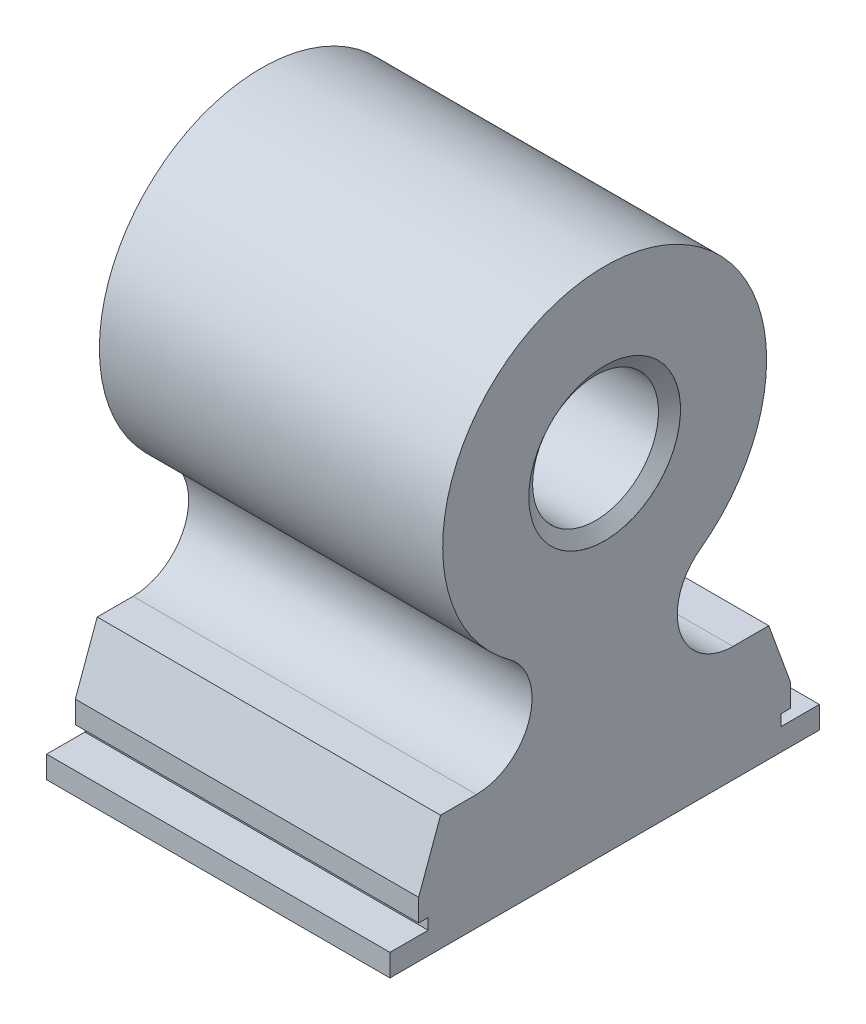
SolidWorks part; units mm, degrees
extrude "Body" add sketch "BodySke" along normal blind 9.4234
sketch "BodySke" plane through (0, 0, 0) normal (1, 0, 0) x (0, 0, -1)
  line L0 (-5.8928, -9.525) -> (5.8928, -9.525)
  line L1 (5.8928, -9.525) -> (5.8928, -8.9154)
  line L2 (5.8928, -8.9154) -> (4.8429, -8.9154)
  line L3 (-5.8928, -9.525) -> (-5.8928, -8.9154)
  line L4 (-5.8928, -8.9154) -> (-4.8429, -8.9154)
  line L5 (4.8429, -8.9154) -> (4.8429, -8.6106)
  line L6 (-4.8429, -8.9154) -> (-4.8429, -8.6106)
  line L7 (4.8429, -8.6106) -> (5.1054, -8.6106)
  line L8 (-4.8429, -8.6106) -> (-5.1054, -8.6106)
  line L9 (-3.5204, -6.35) -> (-4.5045, -6.35)
  line L10 (0, -0.7925) -> (4.5045, -0.7925) construction
  line L11 (4.5045, -6.35) -> (3.5204, -6.35)
  line L12 (0, 7.62) -> (0, -11.43) construction
  line L13 (7.62, 0) -> (-7.62, 0) construction
  line L14 (1.9939, -2.8908) -> (1.9939, -7.62) construction
  line L15 (-1.9939, -2.8908) -> (-1.9939, -7.62) construction
  line L16 (4.5045, -6.35) -> (5.1054, -8.001)
  line L17 (5.1054, -8.001) -> (5.1054, -8.6106)
  line L18 (-4.5045, -6.35) -> (-5.1054, -8.001)
  line L19 (-5.1054, -8.001) -> (-5.1054, -8.6106)
  circle A0 centre (0, 0) radius 1.7272
  arc A1 (2.6205, -3.5904) -> (-2.6205, -3.5904) centre (0, 0) ccw
  arc A2 (3.5204, -6.35) -> (2.6205, -3.5904) centre (3.5204, -4.8235) cw
  arc A3 (-2.6205, -3.5904) -> (-3.5204, -6.35) centre (-3.5204, -4.8235) cw
  dimension "Thread_min" = 3.4544
  dimension "C_dia" = 8.89
  dimension "J_dim" = 3.9878
  dimension "E_dim" = 11.7856
  dimension "D_dim" = 3.175
  dimension "Clinch_ht" = 0.6096
  dimension "Side_ht" = 0.6096
  dimension "Groove_wid" = 0.3048
  dimension "A_dim" = 10.2108
  dimension "Groove_overall" = 9.6859
  dimension "F_dim" = 9.525
  dimension "D12" = 20
  dimension "Advance" = 0.7925
cosmetic thread "ThreadCosmetic" [suppressed]
revolve "EndChamfer" cut sketch "EndChamferSke" angle 360 about L11
sketch "EndChamferSke" plane through (0, 0, 0) normal (0, 0, 1) x (1, 0, 0)
  line L0 (-0.254, 2.0828) -> (0.0025, 2.0828)
  line L2 (0.0025, 2.0828) -> (0.2514, 1.7272)
  line L3 (0.2514, 1.7272) -> (-0.254, 1.7272)
  line L4 (-0.254, 1.7272) -> (-0.254, 2.0828)
  line L5 (9.6774, 2.0828) -> (9.4209, 2.0828)
  line L6 (9.4209, 2.0828) -> (9.172, 1.7272)
  line L7 (9.172, 1.7272) -> (9.6774, 1.7272)
  line L8 (9.6774, 1.7272) -> (9.6774, 2.0828)
  line L9 (0, 4.445) -> (0, -3.5904) construction
  line L10 (9.4234, -3.5904) -> (9.4234, 4.445) construction
  line L11 (-5.1059, 0) -> (14.0173, 0) construction
  line L12 (9.4234, 0) -> (0, 0) construction
  dimension "Thread_min" = 3.4544
  dimension "D3" = 0.254
  dimension "D4" = 0.254
  dimension "Thread_nominal" = 4.1656
  dimension "D2" = 34.99
ref_plane "Plane1" through (0, 0, 0) normal (0, 0, 1) x (1, 0, 0)
ref_plane "Plane2" through (0, 0, 0) normal (0, 1, 0) x (1, 0, 0)
ref_plane "Plane3" through (0, 0, 0) normal (1, 0, 0) x (0, 0, -1)
sketch "ThdSchSke" [suppressed] plane through (0, 0, 0) normal (0, 0, 1) x (1, 0, 0)
  line L0 (-1.2331, 0) -> (11.43, 0) construction
  line L1 (6.0414, 0) -> (0.207, 0) construction
  line L2 (0.0025, 1.7272) -> (0.0025, -1.4224) construction
  line L3 (0.0025, -1.4224) -> (0.2071, -1.1303)
  line L4 (0.207, -1.1303) -> (6.0414, -1.1303) construction
  line L5 (0.0025, -1.4224) -> (-0.202, -1.1303)
  line L6 (-0.202, -1.1303) -> (0.2071, -1.1303)
  line L8 (0.0025, 1.4224) -> (0.0025, -1.4224) construction
  dimension "Thread_nominal" = 4.1656
revolve "ThreadSchematic" [suppressed] cut sketch "ThdSchSke" angle 360 about L0
pattern_linear "ThdSchPat" [suppressed]
equation "' \"Length@Body\" = 0.371"
equation "' \"A_dim@BodySke\" = 0.402"
equation "' \"C_dia@BodySke\" = 0.35"
equation "' \"D_dim@BodySke\" = 0.125"
equation "' \"E_dim@BodySke\" = 0.464"
equation "' \"F_dim@BodySke\" = 0.375"
equation "' \"J_dim@BodySke\" =  0.157"
equation "' \"J_dim@BodySke\" = 0.157"
equation "' \"Advance@BodySke\" = 0.0312"
equation "' \"Thread_min@BodySke\" = 0.136"
equation "' \"Thread_nominal@ThreadCosmetic\" = 0.164"
equation "\"Clinch_ht@BodySke\" = 0.04 * 0.6"
equation "\"Groove_wid@BodySke\" = \"Clinch_ht@BodySke\" / 2"
equation "\"Groove_overall@BodySke\" = \"A_dim@BodySke\" - ( \"E_dim@BodySke\" - \"A_dim@BodySke\") / 3"
equation "\"Side_ht@BodySke\" = \"Clinch_ht@BodySke\""
equation "\"Thread_nominal@EndChamferSke\" = \"Thread_nominal@ThreadCosmetic\""
equation "\"Thread_min@EndChamferSke\" = \"Thread_min@BodySke\""
equation "\"D2@EndChamferSke\" = \"Vee_angle@ThdSchSke\" / 2 - 0.01"
equation "\"Thread_nominal@ThdSchSke\" = \"Thread_nominal@ThreadCosmetic\""
equation "\"Num_threads@ThdSchPat\" = int(  ( \"Length@Body\" - \"Inset@EndChamferSke\" - \"Inset_far@EndChamferSke\" ) / \"Advance@BodySke\" + 0.999 )  + 1"
equation "\"Advance@ThdSchPat\" = (  \"Length@Body\" - \"Inset@EndChamferSke\" - \"Inset_far@EndChamferSke\"  ) /  (\"Num_threads@ThdSchPat\" - 1) 'relax it"
